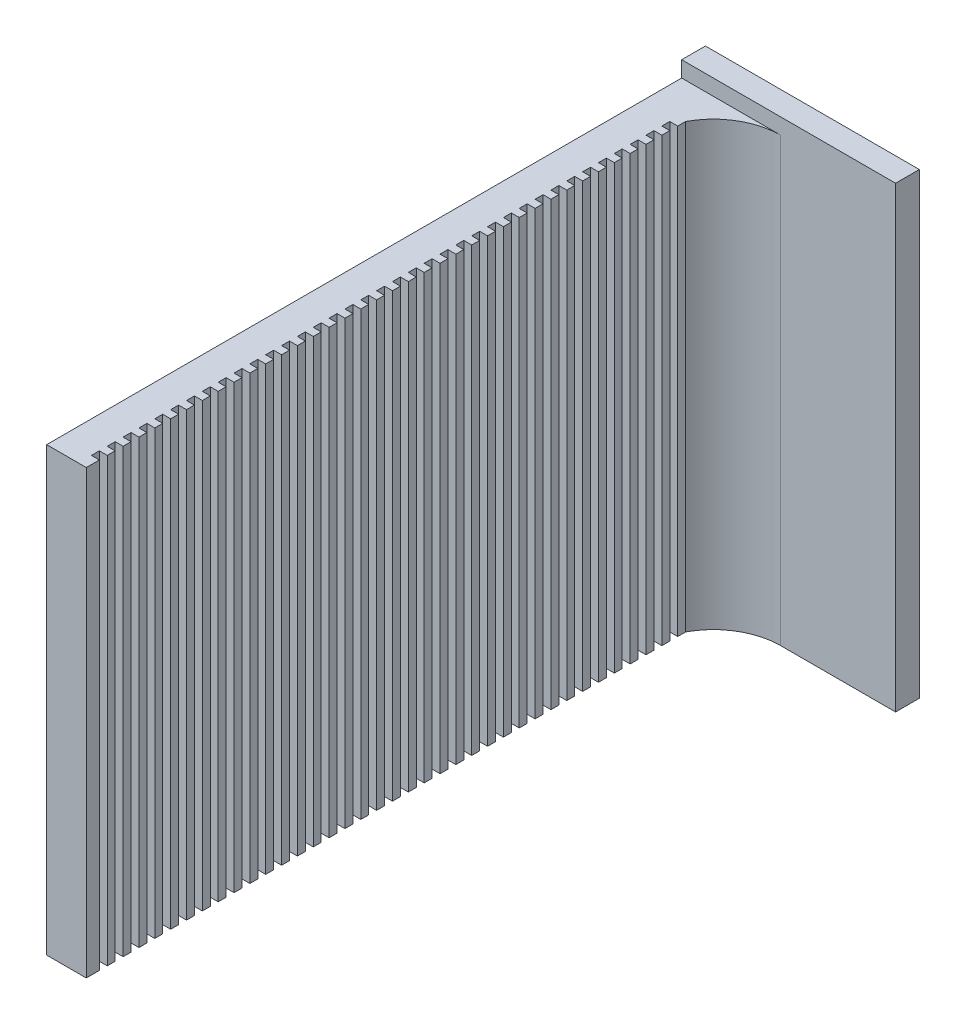
SolidWorks part; units mm, degrees
ref_plane "Front Plane" through (0, 0, 0) normal (0, 0, 1) x (1, 0, 0)
ref_plane "Top Plane" through (0, 0, 0) normal (0, 1, 0) x (1, 0, 0)
ref_plane "Right Plane" through (0, 0, 0) normal (1, 0, 0) x (0, 0, -1)
sketch "Sketch1" plane through (0, 0, 0) normal (0, 1, 0) x (1, 0, 0)
  line L0 (0, 0) -> (0, 80.15)
  line L1 (0, 80.15) -> (22, 80.15)
  line L2 (22, 80.15) -> (22, 83.15)
  line L3 (22, 83.15) -> (0, 83.15)
  line L4 (0, 83.15) -> (-5, 83.15)
  line L5 (-5, 83.15) -> (-5, 0)
  line L6 (-5, 0) -> (0, 0)
  dimension "D1" = 80.15
  dimension "D2" = 5
  dimension "D3" = 22
  dimension "D4" = 3
extrude "Boss-Extrude1" add sketch "Sketch1" along normal blind 55.8
sketch "Sketch2" plane through (0, 55.8, 0) normal (0, 1, 0) x (1, 0, 0)
  line L0 (0, 80.15) -> (7.5, 80.15)
  line L1 (0, 80.15) -> (22, 80.15) construction
  line L2 (0, 80.15) -> (0, 75.65)
  line L3 (0, 0) -> (0, 80.15) construction
  arc A0 (7.5, 80.15) -> (0, 75.65) centre (7.5, 71.65) ccw
  dimension "D1" = 7.5
  dimension "D2" = 4.5
extrude "Boss-Extrude2" add sketch "Sketch2" against normal blind 55.8
sketch "Sketch4" plane through (0, 0, 0) normal (1, 0, 0) x (0, 0, -1)
  line L0 (75.65, 55.8) -> (75.65, 0)
  line L1 (75.65, 0) -> (0, 0)
  line L2 (0, 0) -> (0, 55.8)
  line L3 (0, 55.8) -> (75.65, 55.8)
  line L4 (75.65, 55.8) -> (75.65, 51.15)
  line L5 (75.65, 51.15) -> (75.65, 41.85)
  line L6 (75.65, 41.85) -> (75.65, 32.55)
  line L7 (75.65, 32.55) -> (75.65, 23.25)
  line L8 (75.65, 23.25) -> (75.65, 13.95)
  line L9 (75.65, 13.95) -> (75.65, 4.65)
  line L10 (75.65, 55.8) -> (70.95, 55.8)
  line L11 (70.95, 55.8) -> (70.95, 0)
  circle A0 centre (70.95, 51.15) radius 1.5
  circle A1 centre (70.95, 41.85) radius 1.5
  circle A2 centre (70.95, 32.55) radius 1.5
  circle A3 centre (70.95, 23.25) radius 2.2661
  dimension "D8" = 3
  dimension "D9" = 3
  dimension "D10" = 3
  dimension "D1" = 4.65
  dimension "D2" = 9.3
  dimension "D3" = 9.3
  dimension "D4" = 9.3
  dimension "D5" = 9.3
  dimension "D6" = 9.3
  dimension "D7" = 4.7
sketch "Sketch5" plane through (0, 0, 0) normal (1, 0, 0) x (0, 0, -1)
  line L0 (74.65, 55.8) -> (74.65, 0)
  line L1 (0, 55.8) -> (75.65, 55.8) construction
  line L2 (75.65, 0) -> (0, 0) construction
  line L3 (74.65, 0) -> (73.65, 0)
  line L4 (73.65, 0) -> (73.65, 55.8)
  line L5 (73.65, 55.8) -> (74.65, 55.8)
  dimension "D1" = 1
  dimension "D2" = 1
extrude "Cut-Extrude3" cut sketch "Sketch5" against normal blind 1
pattern_linear "LPattern1" count 37 spacing 2 along (0, 0, 1) of "Cut-Extrude3"
sketch "Sketch6" plane through (0, 55.8, 0) normal (0, 1, 0) x (1, 0, 0)
  line L0 (22, 80.15) -> (-5, 80.15)
  line L1 (-5, 83.15) -> (-5, 0) construction
  line L2 (-5, 80.15) -> (-5, 83.15)
  line L3 (-5, 83.15) -> (22, 83.15)
  line L4 (22, 83.15) -> (22, 80.15)
extrude "Boss-Extrude3" add sketch "Sketch6" along normal blind 2
